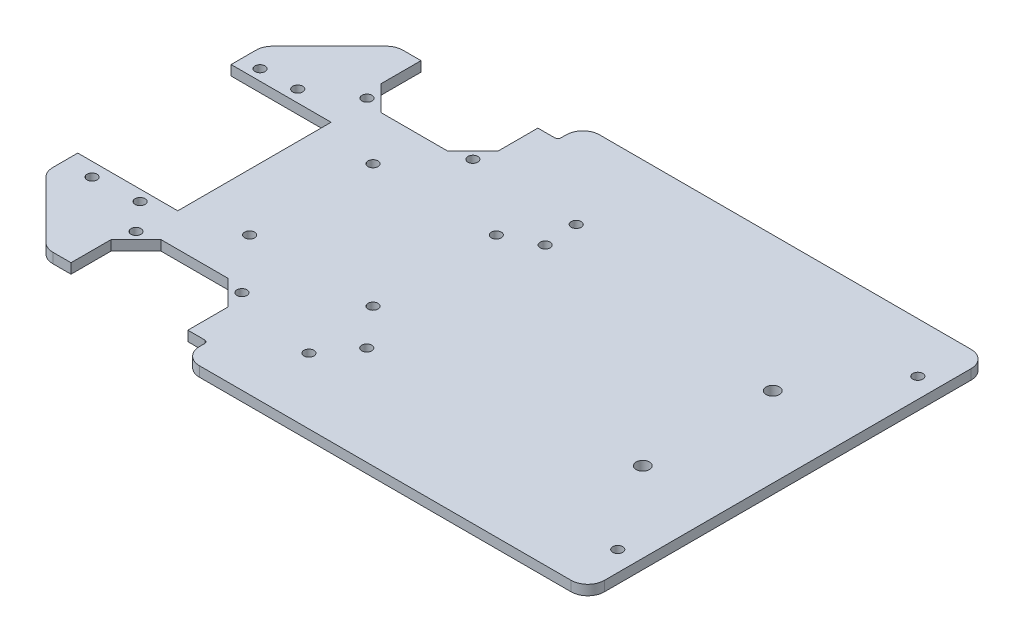
SolidWorks part; units mm, degrees
ref_plane "Front Plane" through (0, 0, 0) normal (0, 0, 1) x (1, 0, 0)
ref_plane "Top Plane" through (0, 0, 0) normal (0, 1, 0) x (1, 0, 0)
ref_plane "Right Plane" through (0, 0, 0) normal (1, 0, 0) x (0, 0, -1)
sketch "Sketch1" plane through (0, 0, 0) normal (0, 1, 0) x (1, 0, 0)
  line L0 (190, 0) -> (0, 0) construction
  line L1 (0, -60) -> (190, -60)
  line L2 (0, -60) -> (0, 60)
  line L3 (0, 60) -> (190, 60)
  line L4 (190, -60) -> (190, 60)
  line L5 (0, -32.5266) -> (27.4734, -60)
  line L6 (30, 23) -> (0, 23) construction
  line L7 (30, 23) -> (30, -23) construction
  line L8 (30, -23) -> (0, -23) construction
  line L9 (0, 23) -> (0, -23)
  line L10 (30, 23) -> (0, -23) construction
  line L11 (30, -23) -> (0, 23) construction
  line L12 (19.9734, -52.5) -> (27.4734, -52.5) construction
  line L13 (68.5266, -52.5) -> (68.5266, -60) construction
  line L14 (35, -33) -> (27.4734, -40.5266) construction
  line L15 (27.4734, -52.5) -> (27.4734, -40.5266) construction
  line L16 (27.4734, -40.5266) -> (27.4734, -52.5) construction
  line L17 (0, 32.5266) -> (27.4734, 60)
  line L18 (35, -33) -> (55, -33) construction
  line L19 (55, -33) -> (62.5266, -40.5266) construction
  line L20 (62.5266, -52.5) -> (68.5266, -52.5) construction
  line L21 (47.5, -37) -> (42.5, -37) construction
  line L22 (45, -37) -> (45, -33) construction
  line L23 (45, -56.5) -> (45, -52.5) construction
  line L24 (39.4, -56.5) -> (50.6, -56.5) construction
  line L25 (27.4734, -52.5) -> (62.5266, -52.5) construction
  line L27 (62.5266, -40.5266) -> (62.5266, -52.5) construction
  point P7 (0, 0)
  point P8 (15, 0)
  dimension "D1" = 120
  dimension "D2" = 190
  dimension "D3" = 30
  dimension "D4" = 23
  dimension "D5" = 10
  dimension "D6" = 20
  dimension "D7" = 45
  dimension "D8" = 45
  dimension "D9" = 45
  dimension "D10" = 7.5
  dimension "D11" = 6
extrude "Boss-Extrude1" add sketch "Sketch1" along normal blind 3 contours L7 L8 L2 L1 L4 L3 L6
sketch "Sketch4" plane through (0, 0, 0) normal (0, 1, 0) x (1, 0, 0)
  line L0 (68.5266, -60) -> (68.5266, -52.5)
  line L1 (68.5266, -52.5) -> (62.5266, -52.5)
  line L2 (62.5266, -52.5) -> (62.5266, -40.5266)
  line L3 (62.5266, -40.5266) -> (55, -33)
  line L4 (55, -33) -> (35, -33)
  line L5 (35, -33) -> (27.4734, -40.5266)
  line L6 (27.4734, -40.5266) -> (27.4734, -52.5)
  line L7 (27.4734, -52.5) -> (19.9734, -52.5)
  line L8 (19.9734, -52.5) -> (27.4734, -60)
  line L9 (27.4734, -60) -> (68.5266, -60)
  line L10 (0, 0) -> (190, 0) construction
  line L11 (190, -60) -> (190, 60) construction
  line L12 (27.4734, 60) -> (68.5266, 60)
  line L13 (19.9734, 52.5) -> (27.4734, 60)
  line L14 (27.4734, 52.5) -> (19.9734, 52.5)
  line L15 (27.4734, 40.5266) -> (27.4734, 52.5)
  line L16 (35, 33) -> (27.4734, 40.5266)
  line L17 (55, 33) -> (35, 33)
  line L18 (62.5266, 40.5266) -> (55, 33)
  line L19 (62.5266, 52.5) -> (62.5266, 40.5266)
  line L20 (68.5266, 52.5) -> (62.5266, 52.5)
  line L21 (68.5266, 60) -> (68.5266, 52.5)
  line L23 (30, 23) -> (0, 23)
  line L24 (30, 23) -> (30, -23)
  line L25 (30, -23) -> (0, -23)
  line L26 (0, 23) -> (0, -23)
extrude "Cut-Extrude1" cut sketch "Sketch4" along normal up to surface (3 mm away) up to face at (72.4911, 3, 0)
fillet "Fillet1" radius 5 8 edges at (190, 1.5, -60) (190, 1.5, 60) (0, 1.5, 32.5266) (0, 1.5, -32.5266) (68.5266, 1.5, 60) (19.9734, 1.5, 52.5) (19.9734, 1.5, -52.5) (68.5266, 1.5, -60)
fillet "Fillet2" radius 1 2 edges at (68.5266, 1.5, -52.5) (68.5266, 1.5, 52.5)
sketch "Sketch5" plane through (0, 0, 0) normal (0, 1, 0) x (1, 0, 0)
  circle A0 centre (47.0626, -18.5) radius 1.5 construction
  circle A1 centre (47.0626, -18.5) radius 1.5
  circle A2 centre (84.0626, -18.5) radius 1.5 construction
  circle A3 centre (84.0626, -18.5) radius 1.5
  circle A4 centre (84.0626, 18.5) radius 1.5 construction
  circle A5 centre (84.0626, 18.5) radius 1.5
  circle A6 centre (47.0626, 18.5) radius 1.5 construction
  circle A7 centre (47.0626, 18.5) radius 1.5
  circle A8 centre (94, 23.2195) radius 1.5 construction
  circle A9 centre (94, 23.2195) radius 1.5
  circle A10 centre (93.3054, 33.2195) radius 1.5 construction
  circle A11 centre (93.3054, 33.2195) radius 1.5
  circle A12 centre (29.1154, 34.642) radius 1.5 construction
  circle A13 centre (60.8846, 34.642) radius 1.5 construction
  circle A14 centre (8.3674, -27.0854) radius 1.5 construction
  circle A15 centre (16.3794, 26.6064) radius 1.5 construction
  circle A16 centre (94, -30.308) radius 1.5 construction
  circle A17 centre (86.6598, -40.308) radius 1.5 construction
  circle A18 centre (29.1154, 34.642) radius 1.5
  circle A19 centre (60.8846, 34.642) radius 1.5
  circle A20 centre (8.3674, -27.0854) radius 1.5
  circle A21 centre (16.3794, 26.6064) radius 1.5
  circle A22 centre (94, -30.308) radius 1.5
  circle A23 centre (86.6598, -40.308) radius 1.5
  circle A24 centre (184, -45) radius 1.5 construction
  circle A25 centre (184, 45) radius 1.5 construction
  circle A26 centre (184, -45) radius 1.5
  circle A27 centre (184, 45) radius 1.5
  circle A28 centre (166, -19.5) radius 2 construction
  circle A29 centre (166, 19.5) radius 2 construction
  circle A30 centre (166, -19.5) radius 2
  circle A31 centre (166, 19.5) radius 2
  circle A32 centre (29.1154, -34.642) radius 1.5 construction
  circle A33 centre (60.8846, -34.642) radius 1.5 construction
  circle A34 centre (29.1154, -34.642) radius 1.5
  circle A35 centre (60.8846, -34.642) radius 1.5
  circle A36 centre (21.9337, -26.25) radius 1.5 construction
  circle A37 centre (5.4397, 26.25) radius 1.5 construction
  circle A38 centre (21.9337, -26.25) radius 1.5
  circle A39 centre (5.4397, 26.25) radius 1.5
extrude "Cut-Extrude2" cut sketch "Sketch5" along normal up to surface (3 mm away) up to face at (55.2686, 3, 0)
